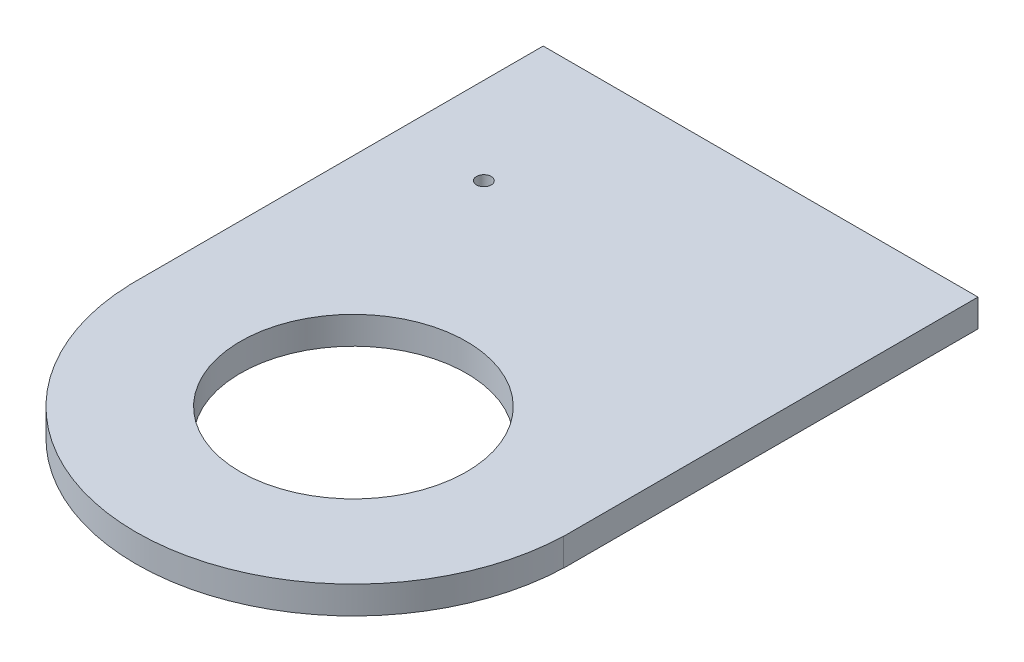
SolidWorks part; units mm, degrees
material "Aleación 6061"
ref_plane "Alzado" through (0, 0, 0) normal (0, 0, 1) x (1, 0, 0)
ref_plane "Planta" through (0, 0, 0) normal (0, 1, 0) x (1, 0, 0)
ref_plane "Vista lateral" through (0, 0, 0) normal (1, 0, 0) x (0, 0, -1)
sketch "Sk_Pared" plane through (0, 0, 0) normal (0, 1, 0) x (1, 0, 0)
  line L1 (-50, -171.65) -> (50, -171.65)
  line L2 (-50, -171.65) -> (-50, -76.35)
  line L3 (-50, -76.35) -> (50, -76.35)
  line L4 (50, -171.65) -> (50, -76.35)
  line L5 (-50, -171.65) -> (50, -76.35) construction
  line L6 (-50, -76.35) -> (50, -171.65) construction
  point P0 (0, -124)
  dimension "D1" = 100
  dimension "D2" = 95.3
  dimension "D3" = 124
extrude "Pared" add sketch "Sk_Pared" along normal blind 6.35 from offset 29.75
sketch "Sk_Cabeza" plane through (0, 0, 0) normal (0, 1, 0) x (1, 0, 0)
  circle A0 centre (0, -170) radius 50
  dimension "D1" = 100
  dimension "D2" = 170
extrude "Cabeza" add sketch "Sk_Cabeza" along normal blind 6.35 from offset 29.75
sketch "Sk_Paso_cubo_J2" plane through (0, 0, 0) normal (0, 1, 0) x (1, 0, 0)
  circle A0 centre (0, -170) radius 26
  dimension "D1" = 52
  dimension "D2" = 170
extrude "Paso_cubo_J2" cut sketch "Sk_Paso_cubo_J2" along normal blind 6.35 from offset 29.75
sketch "Sk_Pasantes_M4_angulos" plane through (0, 0, 0) normal (0, 1, 0) x (1, 0, 0)
  circle A0 centre (-21, -89.11) radius 2.25
  circle A1 centre (21, -89.11) radius 2.25
  dimension "D1" = 4.5
  dimension "D4" = 4.5
  dimension "D2" = 21
  dimension "D3" = 89.11
  dimension "D5" = 21
  dimension "D6" = 89.11
sketch "Sk_Pasante_M3_cincho" plane through (0, 0, 0) normal (0, 1, 0) x (1, 0, 0)
  circle A0 centre (-30, -110) radius 1.7
  dimension "D1" = 3.4
  dimension "D2" = 30
  dimension "D3" = 110
extrude "Pasante_M3_cincho" cut sketch "Sk_Pasante_M3_cincho" along normal blind 6.35 from offset 29.75
sketch "Sk_Rosca_M4_desde_abajo" plane through (0, 0, 76.35) normal (0, 0, -1) x (-1, 0, 0)
  circle A0 centre (35, 34.75) radius 1.65
  circle A1 centre (-35, 34.75) radius 1.65
sketch "Sk_Rosca_M3_desde_abajo" plane through (0, 0, 76.35) normal (0, 0, -1) x (-1, 0, 0)
  circle A0 centre (42, 32.9275) radius 1.25
  circle A1 centre (20, 32.9275) radius 1.25
  circle A2 centre (-20, 32.9275) radius 1.25
  circle A3 centre (-42, 32.9275) radius 1.25
extrude "Rosca_M3_desde_abajo" cut sketch "Sk_Rosca_M3_desde_abajo" against normal blind 9
